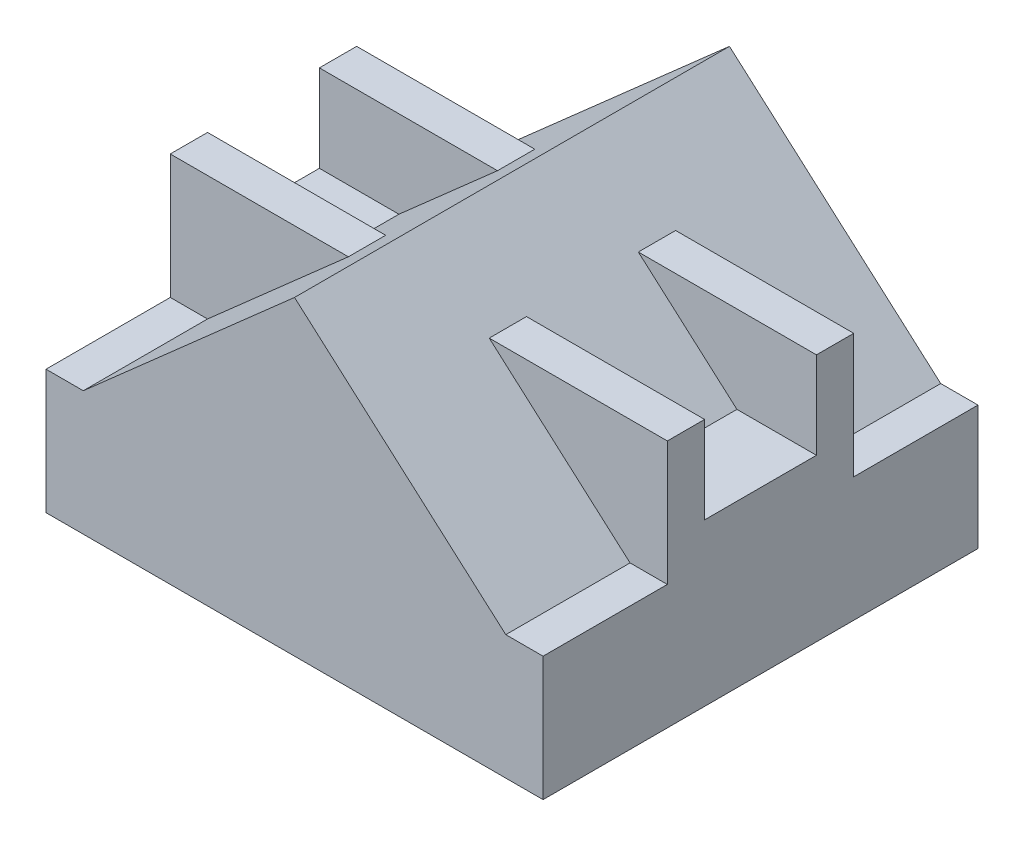
SolidWorks part; units mm, degrees
ref_plane "Front Plane" through (0, 0, 0) normal (0, 0, 1) x (1, 0, 0)
ref_plane "Top Plane" through (0, 0, 0) normal (0, 1, 0) x (1, 0, 0)
ref_plane "Right Plane" through (0, 0, 0) normal (1, 0, 0) x (0, 0, -1)
sketch "Sketch1" plane through (0, 0, 0) normal (0, 1, 0) x (1, 0, 0)
  line L0 (-100, 87.5) -> (-85, 87.5)
  line L1 (100, -87.5) -> (-100, -87.5)
  line L2 (100, -87.5) -> (100, 87.5)
  line L3 (100, 87.5) -> (-100, 87.5)
  line L4 (-100, -87.5) -> (-100, 87.5)
  line L5 (-85, 87.5) -> (-85, 37.5)
  line L6 (-85, 37.5) -> (-100, 37.5)
  line L7 (-85, 37.5) -> (-70, 37.5)
  line L8 (-70, 37.5) -> (-35, 37.5)
  line L9 (-35, 37.5) -> (-35, 22.5)
  line L10 (-35, 22.5) -> (-100, 22.5)
  line L11 (-70, 22.5) -> (-70, -22.5)
  line L12 (-100, -22.5) -> (-35, -22.5)
  line L13 (-35, -22.5) -> (-35, -37.5)
  line L14 (-35, -37.5) -> (-100, -37.5)
  line L15 (-85, -37.5) -> (-85, -87.5)
  line L16 (100, 87.5) -> (85, 87.5)
  line L17 (85, 87.5) -> (85, 37.5)
  line L18 (100, 37.5) -> (70, 37.5)
  line L19 (70, 37.5) -> (35, 37.5)
  line L20 (35, 37.5) -> (35, 22.5)
  line L21 (35, 22.5) -> (100, 22.5)
  line L22 (70, 22.5) -> (70, -22.5)
  line L23 (70, -22.5) -> (100, -22.5)
  line L24 (70, -22.5) -> (35, -22.5)
  line L25 (35, -22.5) -> (35, -37.5)
  line L26 (35, -37.5) -> (100, -37.5)
  line L27 (85, -37.5) -> (85, -87.5)
  line L28 (-85, 37.5) -> (-70, 37.5)
  point P0 (0, 0)
  dimension "D1" = 200
  dimension "D2" = 175
  dimension "D3" = 87.5
  dimension "D4" = 100
  dimension "D5" = 15
  dimension "D6" = 50
  dimension "D7" = 15
  dimension "D8" = 35
  dimension "D9" = 15
  dimension "D10" = 45
  dimension "D11" = 15
  dimension "D12" = 65
  dimension "D13" = 15
  dimension "D14" = 50
  dimension "D15" = 15
  dimension "D16" = 35
  dimension "D17" = 15
  dimension "D18" = 45
  dimension "D19" = 15
  dimension "D20" = 65
extrude "Boss-Extrude3" add sketch "Sketch1" along normal blind 50 contours L27 L26 L25 L24 L22 L21 L20 L19 L18 L17 L3 L5 L7 L8 L9 L10 L11 L12 L13 L14 L15 L1 | L4 L12 L11 L10 | L6 L5 L0 L4 | L10 L9 L8 L7 L6 L4 | L14 L13 L12 L4 | L15 L14 L4 L1 | L18 L2 L3 L17 | L20 L21 L2 L18 L19 | L22 L23 L2 L21 | L25 L26 L2 L23 L24 | L26 L27 L1 L2
sketch "Sketch5" plane through (0, 0, 87.5) normal (0, 0, 1) x (1, 0, 0)
  line L0 (-100, 50) -> (-85, 50)
  line L1 (100, 50) -> (-100, 50) construction
  line L2 (0, 0) -> (0, 125) construction
  line L3 (100, 0) -> (-100, 0) construction
  line L4 (-85, 50) -> (0, 125)
  line L5 (100, 50) -> (85, 50)
  line L6 (85, 50) -> (0, 125)
  line L11 (-100, 0) -> (100, 0)
  line L12 (100, 0) -> (100, 50)
  line L13 (100, 50) -> (-100, 50)
  line L14 (-100, 50) -> (-100, 0)
  line L15 (-100, 0) -> (100, 0)
  line L16 (100, 0) -> (100, 50)
  line L18 (-100, 50) -> (-100, 0)
  dimension "D1" = 15
  dimension "D2" = 125
  dimension "D3" = 15
  dimension "D4" = 0
extrude "Boss-Extrude4" add sketch "Sketch5" against normal blind 175 contours L6 L4 L0 L18 L15 L16 L5
sketch "Sketch18" plane through (0, 0, 0) normal (1, 0, 0) x (0, 0, -1)
  line L0 (-87.5, 50) -> (-37.5, 50)
  line L1 (87.5, 50) -> (-87.5, 50) construction
  line L2 (-37.5, 50) -> (-37.5, 100)
  line L3 (-37.5, 100) -> (-22.5, 100)
  line L4 (-22.5, 100) -> (-22.5, 65)
  line L5 (-22.5, 65) -> (22.5, 65)
  line L6 (22.5, 65) -> (22.5, 100)
  line L7 (22.5, 100) -> (37.5, 100)
  line L8 (37.5, 100) -> (37.5, 50)
  line L9 (-87.5, 50) -> (87.5, 50) construction
  line L10 (37.5, 50) -> (87.5, 50)
  line L11 (-87.5, 50) -> (-87.5, 0)
  line L12 (-87.5, 0) -> (87.5, 0)
  line L13 (87.5, 0) -> (87.5, 50)
  dimension "D1" = 50
  dimension "D2" = 50
  dimension "D3" = 15
  dimension "D4" = 35
  dimension "D5" = 45
  dimension "D6" = 35
  dimension "D7" = 15
extrude "Boss-Extrude6" add sketch "Sketch18" along normal mid plane 200
